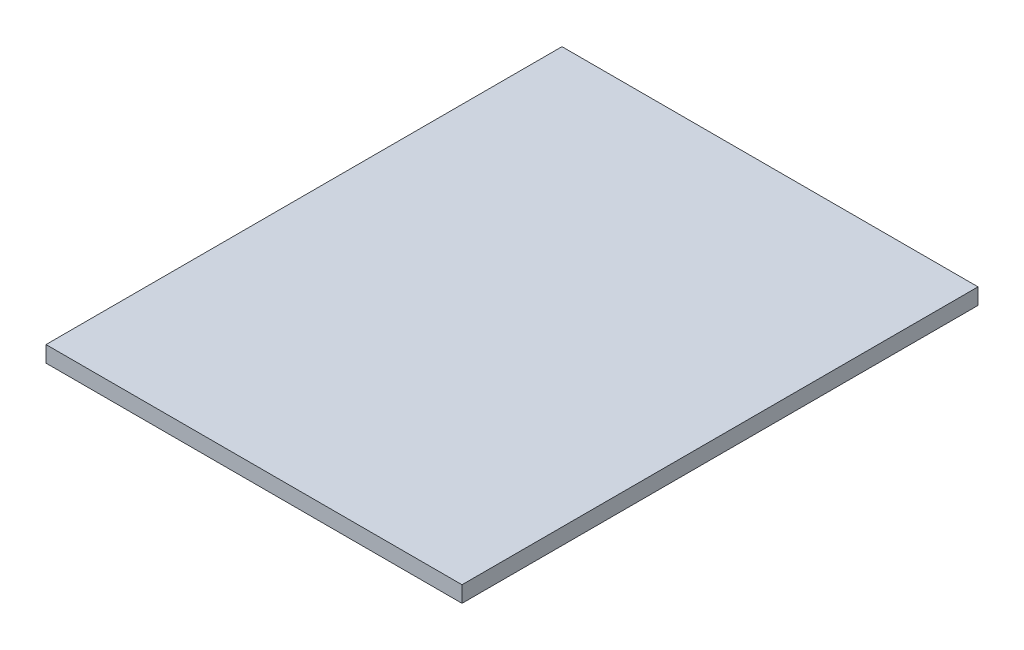
SolidWorks part; units mm, degrees
material "Oak"
ref_plane "Front Plane" through (0, 0, 0) normal (0, 0, 1) x (1, 0, 0)
ref_plane "Top Plane" through (0, 0, 0) normal (0, 1, 0) x (1, 0, 0)
ref_plane "Right Plane" through (0, 0, 0) normal (1, 0, 0) x (0, 0, -1)
sketch "Sketch1" plane through (0, 0, 0) normal (0, 1, 0) x (1, 0, 0)
  line L1 (-163.83, -203.2) -> (163.83, -203.2)
  line L2 (-163.83, -203.2) -> (-163.83, 203.2)
  line L3 (-163.83, 203.2) -> (163.83, 203.2)
  line L4 (163.83, -203.2) -> (163.83, 203.2)
  line L5 (-163.83, -203.2) -> (163.83, 203.2) construction
  line L6 (-163.83, 203.2) -> (163.83, -203.2) construction
  point P0 (0, 0)
  dimension "D1" = 406.4
  dimension "D2" = 327.66
extrude "Boss-Extrude1" add sketch "Sketch1" along normal blind 12.7 contours L3 L4 L1 L2
